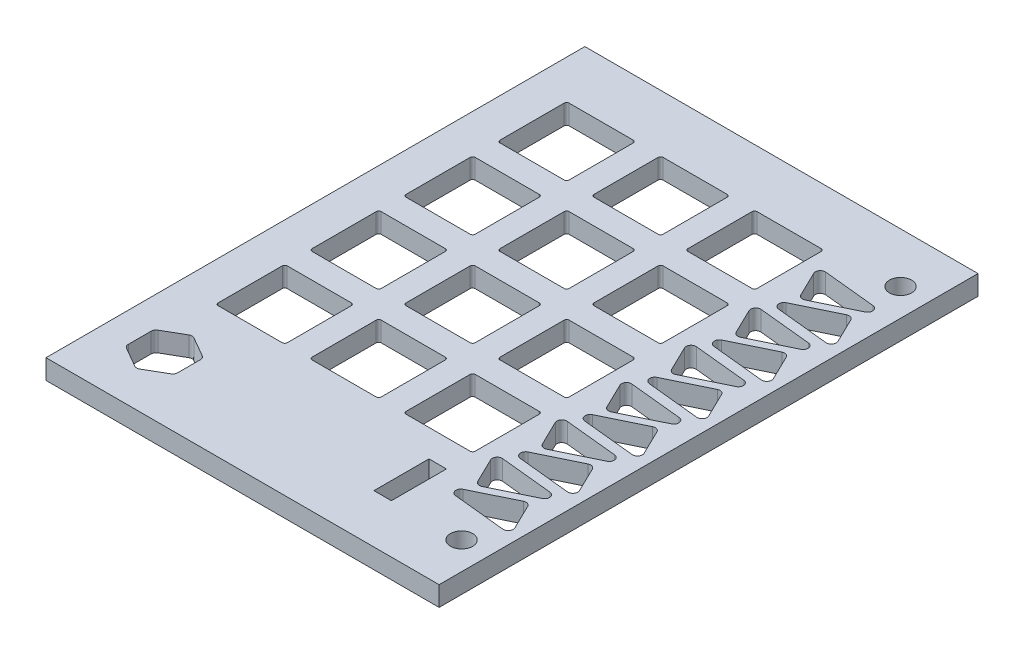
SolidWorks part; units mm, degrees
material "ABS"
ref_plane "Piano frontale" through (0, 0, 0) normal (0, 0, 1) x (1, 0, 0)
ref_plane "Piano superiore" through (0, 0, 0) normal (0, 1, 0) x (1, 0, 0)
ref_plane "Piano destro" through (0, 0, 0) normal (1, 0, 0) x (0, 0, -1)
sketch "Schizzo1" plane through (0, 0, 0) normal (0, 1, 0) x (1, 0, 0)
  line L1 (-45.875, 54.625) -> (42.8273, 54.625)
  line L2 (-45.875, 54.625) -> (-45.875, -54.625)
  line L3 (-45.875, -54.625) -> (42.8273, -54.625)
  line L4 (42.8273, 54.625) -> (42.8273, -54.625)
  point P4 (0, 0)
  dimension "D1" = 88.7023
  dimension "D2" = 109.25
  dimension "D3" = 45.875
  dimension "D4" = 54.625
extrude "Estrusione-Estrusione1" add sketch "Schizzo1" along normal blind 4
sketch "Schizzo2" plane through (0, 0, 0) normal (0, -1, 0) x (1, 0, 0)
  line L0 (42.8273, 54.625) -> (42.8273, -54.625) construction
  line L1 (42.8273, -54.625) -> (-45.875, -54.625) construction
  line L2 (9.55, -29.6) -> (22.55, -42.6) construction
  point P0 (16.05, -36.1)
  point P8 (16.05, -36.1)
  line B0 (-31.575, -45.625) -> (25.575, -45.625)
  line B1 (-28.55, 28.05) -> (-15.55, 28.05)
  line B2 (-28.55, 14.05) -> (-15.55, 14.05)
  line B3 (-29.05, 27.55) -> (-29.05, 14.55)
  line B4 (-15.05, 27.55) -> (-15.05, 14.55)
  line B5 (-9.5, 28.05) -> (3.5, 28.05)
  line B6 (-9.5, 14.05) -> (3.5, 14.05)
  line B7 (-10, 27.55) -> (-10, 14.55)
  line B8 (4, 27.55) -> (4, 14.55)
  line B9 (9.55, 28.05) -> (22.55, 28.05)
  line B10 (9.55, 14.05) -> (22.55, 14.05)
  line B11 (9.05, 27.55) -> (9.05, 14.55)
  line B12 (23.05, 27.55) -> (23.05, 14.55)
  line B13 (-28.55, 9) -> (-15.55, 9)
  line B14 (-28.55, -5) -> (-15.55, -5)
  line B15 (-29.05, 8.5) -> (-29.05, -4.5)
  line B16 (-15.05, 8.5) -> (-15.05, -4.5)
  line B17 (-9.5, 9) -> (3.5, 9)
  line B18 (-9.5, -5) -> (3.5, -5)
  line B19 (-10, 8.5) -> (-10, -4.5)
  line B20 (4, 8.5) -> (4, -4.5)
  line B21 (9.55, 9) -> (22.55, 9)
  line B22 (9.55, -5) -> (22.55, -5)
  line B23 (9.05, 8.5) -> (9.05, -4.5)
  line B24 (23.05, 8.5) -> (23.05, -4.5)
  line B25 (-28.55, -10.05) -> (-15.55, -10.05)
  line B26 (-28.55, -24.05) -> (-15.55, -24.05)
  line B27 (-29.05, -10.55) -> (-29.05, -23.55)
  line B28 (-15.05, -10.55) -> (-15.05, -23.55)
  line B29 (-9.5, -10.05) -> (3.5, -10.05)
  line B30 (-9.5, -24.05) -> (3.5, -24.05)
  line B31 (-10, -10.55) -> (-10, -23.55)
  line B32 (4, -10.55) -> (4, -23.55)
  line B33 (9.55, -10.05) -> (22.55, -10.05)
  line B34 (9.55, -24.05) -> (22.55, -24.05)
  line B35 (9.05, -10.55) -> (9.05, -23.55)
  line B36 (23.05, -10.55) -> (23.05, -23.55)
  line B37 (-28.55, -29.1) -> (-15.55, -29.1)
  line B38 (-28.55, -43.1) -> (-15.55, -43.1)
  line B39 (-29.05, -29.6) -> (-29.05, -42.6)
  line B40 (-15.05, -29.6) -> (-15.05, -42.6)
  line B41 (-9.5, -29.1) -> (3.5, -29.1)
  line B42 (-9.5, -43.1) -> (3.5, -43.1)
  line B43 (-10, -29.6) -> (-10, -42.6)
  line B44 (4, -29.6) -> (4, -42.6)
  line B45 (9.55, -29.1) -> (22.55, -29.1)
  line B46 (9.55, -43.1) -> (22.55, -43.1)
  line B47 (9.05, -29.6) -> (9.05, -42.6)
  line B48 (23.05, -29.6) -> (23.05, -42.6)
  line B49 (-31.575, 30.575) -> (25.575, 30.575)
  line B50 (-31.575, -45.625) -> (-31.575, 30.575)
  line B51 (25.575, -45.625) -> (25.575, 30.575)
  arc B52 (-28.55, 28.05) -> (-29.05, 27.55) centre (-28.55, 27.55) ccw
  arc B53 (-15.05, 27.55) -> (-15.55, 28.05) centre (-15.55, 27.55) ccw
  arc B54 (-29.05, 14.55) -> (-28.55, 14.05) centre (-28.55, 14.55) ccw
  arc B55 (-15.55, 14.05) -> (-15.05, 14.55) centre (-15.55, 14.55) ccw
  arc B56 (-9.5, 28.05) -> (-10, 27.55) centre (-9.5, 27.55) ccw
  arc B57 (4, 27.55) -> (3.5, 28.05) centre (3.5, 27.55) ccw
  arc B58 (-10, 14.55) -> (-9.5, 14.05) centre (-9.5, 14.55) ccw
  arc B59 (3.5, 14.05) -> (4, 14.55) centre (3.5, 14.55) ccw
  arc B60 (9.55, 28.05) -> (9.05, 27.55) centre (9.55, 27.55) ccw
  arc B61 (23.05, 27.55) -> (22.55, 28.05) centre (22.55, 27.55) ccw
  arc B62 (9.05, 14.55) -> (9.55, 14.05) centre (9.55, 14.55) ccw
  arc B63 (22.55, 14.05) -> (23.05, 14.55) centre (22.55, 14.55) ccw
  arc B64 (-28.55, 9) -> (-29.05, 8.5) centre (-28.55, 8.5) ccw
  arc B65 (-15.05, 8.5) -> (-15.55, 9) centre (-15.55, 8.5) ccw
  arc B66 (-29.05, -4.5) -> (-28.55, -5) centre (-28.55, -4.5) ccw
  arc B67 (-15.55, -5) -> (-15.05, -4.5) centre (-15.55, -4.5) ccw
  arc B68 (-9.5, 9) -> (-10, 8.5) centre (-9.5, 8.5) ccw
  arc B69 (4, 8.5) -> (3.5, 9) centre (3.5, 8.5) ccw
  arc B70 (-10, -4.5) -> (-9.5, -5) centre (-9.5, -4.5) ccw
  arc B71 (3.5, -5) -> (4, -4.5) centre (3.5, -4.5) ccw
  arc B72 (9.55, 9) -> (9.05, 8.5) centre (9.55, 8.5) ccw
  arc B73 (23.05, 8.5) -> (22.55, 9) centre (22.55, 8.5) ccw
  arc B74 (9.05, -4.5) -> (9.55, -5) centre (9.55, -4.5) ccw
  arc B75 (22.55, -5) -> (23.05, -4.5) centre (22.55, -4.5) ccw
  arc B76 (-28.55, -10.05) -> (-29.05, -10.55) centre (-28.55, -10.55) ccw
  arc B77 (-15.05, -10.55) -> (-15.55, -10.05) centre (-15.55, -10.55) ccw
  arc B78 (-29.05, -23.55) -> (-28.55, -24.05) centre (-28.55, -23.55) ccw
  arc B79 (-15.55, -24.05) -> (-15.05, -23.55) centre (-15.55, -23.55) ccw
  arc B80 (-9.5, -10.05) -> (-10, -10.55) centre (-9.5, -10.55) ccw
  arc B81 (4, -10.55) -> (3.5, -10.05) centre (3.5, -10.55) ccw
  arc B82 (-10, -23.55) -> (-9.5, -24.05) centre (-9.5, -23.55) ccw
  arc B83 (3.5, -24.05) -> (4, -23.55) centre (3.5, -23.55) ccw
  arc B84 (9.55, -10.05) -> (9.05, -10.55) centre (9.55, -10.55) ccw
  arc B85 (23.05, -10.55) -> (22.55, -10.05) centre (22.55, -10.55) ccw
  arc B86 (9.05, -23.55) -> (9.55, -24.05) centre (9.55, -23.55) ccw
  arc B87 (22.55, -24.05) -> (23.05, -23.55) centre (22.55, -23.55) ccw
  arc B88 (-28.55, -29.1) -> (-29.05, -29.6) centre (-28.55, -29.6) ccw
  arc B89 (-15.05, -29.6) -> (-15.55, -29.1) centre (-15.55, -29.6) ccw
  arc B90 (-29.05, -42.6) -> (-28.55, -43.1) centre (-28.55, -42.6) ccw
  arc B91 (-15.55, -43.1) -> (-15.05, -42.6) centre (-15.55, -42.6) ccw
  arc B92 (-9.5, -29.1) -> (-10, -29.6) centre (-9.5, -29.6) ccw
  arc B93 (4, -29.6) -> (3.5, -29.1) centre (3.5, -29.6) ccw
  arc B94 (-10, -42.6) -> (-9.5, -43.1) centre (-9.5, -42.6) ccw
  arc B95 (3.5, -43.1) -> (4, -42.6) centre (3.5, -42.6) ccw
  arc B96 (9.55, -29.1) -> (9.05, -29.6) centre (9.55, -29.6) ccw
  arc B97 (23.05, -29.6) -> (22.55, -29.1) centre (22.55, -29.6) ccw
  arc B98 (9.05, -42.6) -> (9.55, -43.1) centre (9.55, -42.6) ccw
  arc B99 (22.55, -43.1) -> (23.05, -42.6) centre (22.55, -42.6) ccw
  dimension "D1" = 26.7773
  dimension "D2" = 18.525
sketch_block_instance "plate-2026-08-13T19_05_16.025Z-1"
sketch_block "plate-2026-08-13T19_05_16.025Z"
extrude "Taglio-Estrusione1" cut sketch "Schizzo2" against normal blind 20
sketch "Schizzo3" plane through (0, 0, 0) normal (0, -1, 0) x (1, 0, 0)
  line L0 (-37.25, -44.5) -> (37.25, -44.5) construction
  line L1 (37.25, -44.5) -> (37.25, 44.5) construction
  line L2 (37.25, 44.5) -> (-37.25, 44.5) construction
  line L3 (-37.25, 44.5) -> (-37.25, -44.5) construction
  circle A7 centre (37.25, 44.5) radius 2.25
  circle A9 centre (37.25, -44.5) radius 2.25
  dimension "D1" = 74.5
  dimension "D3" = 4.5
  dimension "D2" = 89
  dimension "D4" = 44.5
  dimension "D5" = 37.25
extrude "Taglio-Estrusione2" cut sketch "Schizzo3" against normal blind 10
sketch "Schizzo4" plane through (0, 0, 0) normal (0, -1, 0) x (1, 0, 0)
  line L19 (25.3501, -39.625) -> (41.3273, -39.625) construction
  line L20 (41.3273, -39.625) -> (41.3273, 24.5888) construction
  line L21 (25.3501, 25.875) -> (41.3273, 27.5031)
  line L22 (25.3501, -39.625) -> (25.3501, 38.6031) construction
  line L23 (25.3501, 12.775) -> (29.0455, 20.375)
  line L25 (29.0455, 20.375) -> (41.3273, 14.4031)
  line L26 (41.3273, 14.4031) -> (25.3501, 12.775)
  line L27 (25.3501, 10.775) -> (41.3273, 12.4031)
  line L28 (41.3273, 12.4031) -> (37.6319, 4.8031)
  line L29 (37.6319, 4.8031) -> (25.3501, 10.775)
  line L33 (41.3273, 1.3031) -> (29.0455, 7.275)
  line L34 (29.0455, 7.275) -> (25.3501, -0.325)
  line L35 (25.3501, -0.325) -> (41.3273, 1.3031)
  line L36 (25.3501, -2.325) -> (41.3273, -0.6969)
  line L37 (41.3273, -0.6969) -> (37.6319, -8.2969)
  line L38 (37.6319, -8.2969) -> (25.3501, -2.325)
  line L39 (29.0455, -5.825) -> (41.3273, -11.7969)
  line L40 (41.3273, -11.7969) -> (25.3501, -13.425)
  line L41 (25.3501, -13.425) -> (29.0455, -5.825)
  line L42 (25.3501, -15.425) -> (41.3273, -13.7969)
  line L43 (41.3273, -13.7969) -> (37.6319, -21.3969)
  line L44 (37.6319, -21.3969) -> (25.3501, -15.425)
  line L45 (29.0455, -18.925) -> (41.3273, -24.8969)
  line L46 (41.3273, -24.8969) -> (25.3501, -26.525)
  line L47 (25.3501, -26.525) -> (29.0455, -18.925)
  line L48 (25.3501, -28.525) -> (41.3273, -26.8969)
  line L49 (41.3273, -26.8969) -> (37.6319, -34.4969)
  line L50 (37.6319, -34.4969) -> (25.3501, -28.525)
  line L51 (29.0455, -32.025) -> (41.3273, -37.9969)
  line L52 (41.3273, -37.9969) -> (25.3501, -39.625)
  line L53 (25.3501, -39.625) -> (29.0455, -32.025)
  line L55 (25.3501, 38.6031) -> (41.3273, 38.6031) construction
  line L56 (41.3273, 38.6031) -> (41.3273, 24.5888) construction
  line L57 (25.3501, 23.875) -> (37.6319, 17.9031)
  line L58 (37.6319, 17.9031) -> (41.3273, 25.5031)
  line L59 (41.3273, 25.5031) -> (25.3501, 23.875)
  line L60 (41.3273, 27.5031) -> (29.0455, 33.475)
  line L61 (29.0455, 33.475) -> (25.3501, 25.875)
  line L62 (25.3501, 36.975) -> (37.6319, 31.0031)
  line L63 (37.6319, 31.0031) -> (41.3273, 38.6031)
  line L64 (41.3273, 38.6031) -> (25.3501, 36.975)
  line L66 (42.8273, 54.625) -> (42.8273, -54.625) construction
  line L67 (42.8273, -54.625) -> (-45.875, -54.625) construction
  dimension "D14" = 2
  dimension "D1" = 2
  dimension "D2" = 1.5
  dimension "D3" = 2
  dimension "D4" = 15
  dimension "D5" = 3.5
  dimension "D6" = 3.5
  dimension "D7" = 2
  dimension "D8" = 3.5
  dimension "D9" = 2
  dimension "D10" = 3.5
  dimension "D11" = 3.5
  dimension "D13" = 13.6568
  dimension "D15" = 3.5
  dimension "D16" = 7.6
extrude "Taglio-Estrusione3" cut sketch "Schizzo4" against normal blind 10
fillet "Raccordo1" radius 1 36 edges at (41.3273, 2, -37.9969) (25.3501, 2, -39.625) (29.0455, 2, -32.025) (41.3273, 2, -26.8969) (25.3501, 2, -28.525) (37.6319, 2, -34.4969) (41.3273, 2, -24.8969) (25.3501, 2, -26.525) (29.0455, 2, -18.925) (41.3273, 2, -13.7969) (37.6319, 2, -21.3969) (25.3501, 2, -15.425) (25.3501, 2, -13.425) (29.0455, 2, -5.825) (41.3273, 2, -11.7969) (37.6319, 2, -8.2969) (41.3273, 2, -0.6969) (25.3501, 2, -2.325) (25.3501, 2, -0.325) (29.0455, 2, 7.275) (41.3273, 2, 1.3031) (37.6319, 2, 4.8031) (41.3273, 2, 12.4031) (25.3501, 2, 10.775) (41.3273, 2, 14.4031) (25.3501, 2, 12.775) (29.0455, 2, 20.375) (25.3501, 2, 36.975) (41.3273, 2, 38.6031) (37.6319, 2, 31.0031) (29.0455, 2, 33.475) (41.3273, 2, 27.5031) (41.3273, 2, 25.5031) (37.6319, 2, 17.9031) (25.3501, 2, 23.875) (25.3501, 2, 25.875)
sketch "Schizzo5" plane through (0, 4, 0) normal (0, 1, 0) x (1, 0, 0)
  line L0 (42.8273, 54.625) -> (-45.875, 54.625) construction
  line L1 (-45.875, -54.625) -> (-36.875, -54.625)
  line L2 (-45.875, -54.625) -> (-45.875, 54.625)
  line L3 (-45.875, 54.625) -> (-36.875, 54.625)
  line L4 (-36.875, -54.625) -> (-36.875, 54.625)
  dimension "D1" = 9
extrude "Taglio-Estrusione4" cut sketch "Schizzo5" against normal blind 10
sketch "Schizzo7" plane through (0, 4, 0) normal (0, 1, 0) x (1, 0, 0)
  line L0 (22.7525, -44.2275) -> (22.7525, -34.0675) construction
  line L2 (22.7525, -34.0675) -> (20.2125, -34.0675) construction
  line L3 (20.2125, -34.0675) -> (20.2125, -44.2275) construction
  line L4 (20.2125, -44.2275) -> (22.7525, -44.2275) construction
  line L5 (-36.875, -54.625) -> (42.8273, -54.625) construction
  line L6 (19.7125, -44.7275) -> (23.2525, -44.7275)
  line L7 (23.2525, -44.7275) -> (23.2525, -33.5675)
  line L8 (23.2525, -33.5675) -> (19.7125, -33.5675)
  line L9 (19.7125, -33.5675) -> (19.7125, -44.7275)
  line L10 (42.8273, -54.625) -> (42.8273, 54.625) construction
  dimension "D1" = 2.54
  dimension "D2" = 10.16
  dimension "D3" = 10.3975
  dimension "D4" = 0.5
  dimension "D5" = 0.5
  dimension "D6" = 0.5
  dimension "D7" = 0.5
  dimension "D8" = 20.0748
extrude "Taglio-Estrusione5" cut sketch "Schizzo7" against normal blind 12.7
sketch "Schizzo8" plane through (0, 4, 0) normal (0, 1, 0) x (1, 0, 0)
  line L0 (-36.875, -54.625) -> (-36.875, 54.625) construction
  line L1 (-25.875, -47.3985) -> (-20.875, -44.5118)
  line L2 (-20.875, -44.5118) -> (-20.875, -38.7382)
  line L3 (-20.875, -38.7382) -> (-25.875, -35.8515)
  line L4 (-25.875, -35.8515) -> (-30.875, -38.7382)
  line L5 (-30.875, -38.7382) -> (-30.875, -44.5118)
  line L6 (-30.875, -44.5118) -> (-25.875, -47.3985)
  line L7 (-36.875, -54.625) -> (42.8273, -54.625) construction
  line L8 (-25.875, -35.8515) -> (-25.875, -47.3985) construction
  circle A0 centre (-25.875, -41.625) radius 5 construction
  dimension "D1" = 10
  dimension "D2" = 11
  dimension "D3" = 13
extrude "Taglio-Estrusione6" cut sketch "Schizzo8" against normal blind 10
fillet "Raccordo2" radius 1 6 edges at (-30.875, 2, 44.5118) (-30.875, 2, 38.7382) (-25.875, 2, 35.8515) (-20.875, 2, 38.7382) (-20.875, 2, 44.5118) (-25.875, 2, 47.3985)
